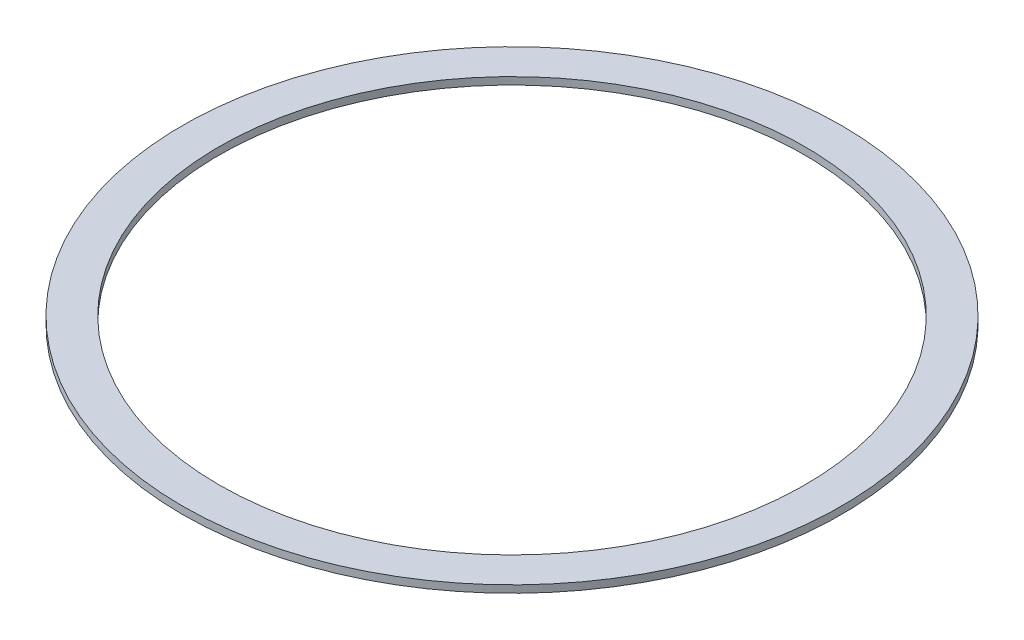
SolidWorks part; units mm, degrees
ref_plane "前视基准面" through (0, 0, 0) normal (0, 0, 1) x (1, 0, 0)
ref_plane "上视基准面" through (0, 0, 0) normal (0, 1, 0) x (1, 0, 0)
ref_plane "右视基准面" through (0, 0, 0) normal (1, 0, 0) x (0, 0, -1)
other "Configuration Table"
sketch "草图1" plane through (0, 0, 0) normal (0, 1, 0) x (1, 0, 0)
  circle A0 centre (0, 0) radius 20
  circle A1 centre (0, 0) radius 22.5
  dimension "D1" = 40
  dimension "D2" = 45
extrude "凸台-拉伸1" add sketch "草图1" along normal blind 0.5
